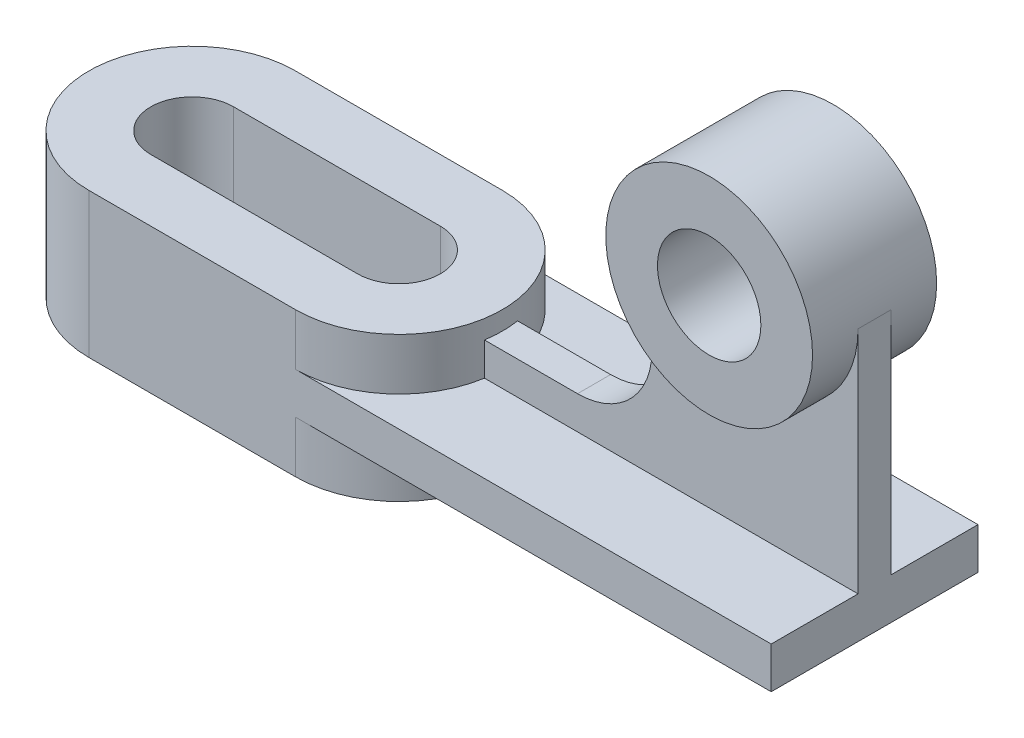
SolidWorks part; units mm, degrees
ref_plane "Front Plane" through (0, 0, 0) normal (0, 0, 1) x (1, 0, 0)
ref_plane "Top Plane" through (0, 0, 0) normal (0, 1, 0) x (1, 0, 0)
ref_plane "Right Plane" through (0, 0, 0) normal (1, 0, 0) x (0, 0, -1)
sketch "Sketch1" plane through (0, 0, 0) normal (0, 1, 0) x (1, 0, 0)
  line L0 (-15.6584, 0) -> (34.3416, 0) construction
  line L1 (-15.6584, 25) -> (34.3416, 25)
  line L2 (-15.6584, -25) -> (34.3416, -25)
  line L3 (-15.6584, 0) -> (34.3416, 0) construction
  line L4 (-15.6584, 10) -> (34.3416, 10)
  line L5 (-15.6584, -10) -> (34.3416, -10)
  arc A0 (-15.6584, 25) -> (-15.6584, -25) centre (-15.6584, 0) ccw
  arc A1 (34.3416, -25) -> (34.3416, 25) centre (34.3416, 0) ccw
  arc A2 (-15.6584, 10) -> (-15.6584, -10) centre (-15.6584, 0) ccw
  arc A3 (34.3416, -10) -> (34.3416, 10) centre (34.3416, 0) ccw
  point P3 (9.3416, 0)
  point P10 (9.3416, 0)
  dimension "D2" = 50
  dimension "D3" = 10
  dimension "D1" = 50
extrude "Boss-Extrude1" add sketch "Sketch1" against normal blind 35
sketch "Sketch2" plane through (0, 0, 25) normal (0, 0, 1) x (1, 0, 0)
  line L0 (34.3416, -35) -> (34.3416, 0) construction
  line L1 (34.3416, -12.5) -> (149.3416, -12.5)
  line L2 (34.3416, -12.5) -> (34.3416, -22.5)
  line L3 (34.3416, -22.5) -> (149.3416, -22.5)
  line L4 (149.3416, -12.5) -> (149.3416, -22.5)
  line L5 (-40.6584, 0) -> (-40.6584, -35)
  line L6 (59.3416, 0) -> (59.3416, -12.5)
  line L7 (59.3416, -35) -> (59.3416, 0) construction
  line L8 (59.3416, -35) -> (59.3416, -22.5)
  line M10 (34.3416, -35) -> (34.3416, 0)
  dimension "D1" = 10
  dimension "D2" = 190
extrude "Boss-Extrude2" add sketch "Sketch2" against normal blind 50 contours L4 L1 L3 M10
ref_plane "Plane1" through (0, 0, 0) normal (0, 0, 1) x (1, 0, 0)
sketch "Sketch3" plane through (0, 0, 0) normal (0, 0, 1) x (1, 0, 0)
  line L0 (59.3416, -12.5) -> (149.3416, -12.5)
  line L2 (149.3416, -12.5) -> (149.3416, 43)
  line L3 (99.3416, 43) -> (99.3416, 11.0447)
  line L6 (58.5249, -4.5) -> (81.5099, -4.5)
  line L7 (58.5249, -4.5) -> (58.5249, -12.5)
  line L8 (58.5249, -12.5) -> (59.3416, -12.5)
  arc A0 (81.5099, -4.5) -> (99.3416, 11.0447) centre (81.5099, 13.5) ccw
  circle A1 centre (124.3416, 43) radius 25
  circle A2 centre (124.3416, 43) radius 12.5
  dimension "D1" = 50
  dimension "D2" = 18
  dimension "D3" = 55.5
extrude "Boss-Extrude4" add sketch "Sketch3" along normal mid plane 8 contours A1 L3 A0 L6 L7 L8 L0 L2
sketch "Sketch4" plane through (0, 0, 0) normal (0, 0, 1) x (1, 0, 0)
  circle A0 centre (124.3416, 43) radius 25
  circle A1 centre (124.3416, 43) radius 12.5
extrude "Boss-Extrude5" add sketch "Sketch4" along normal mid plane 30
